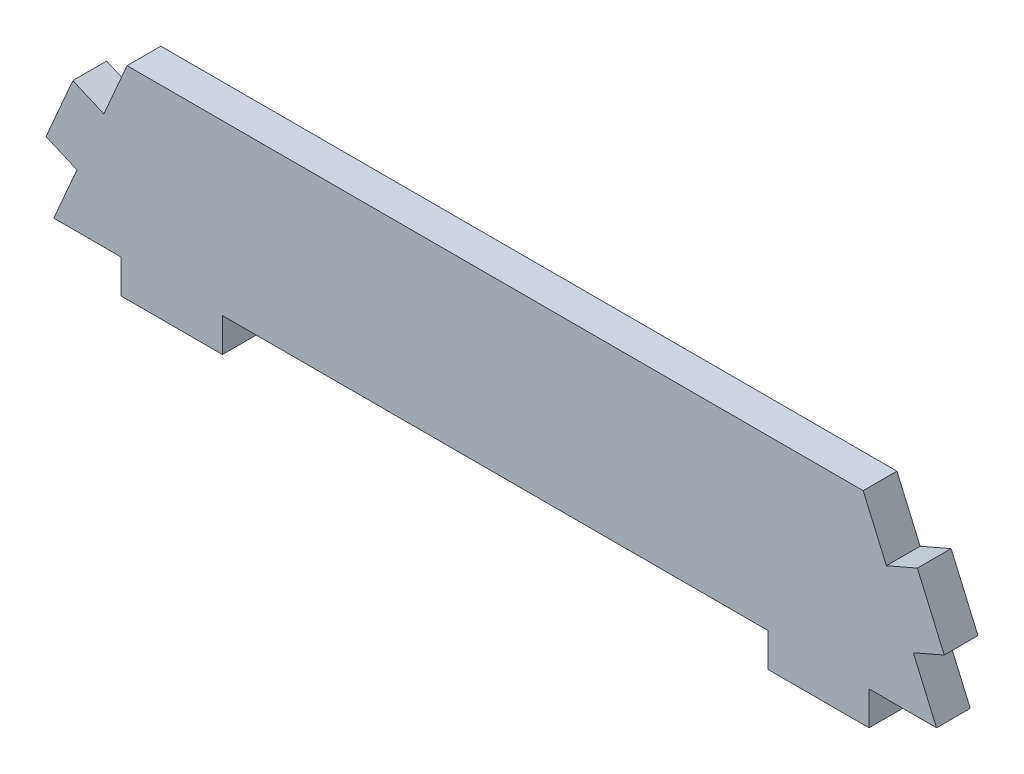
SolidWorks part; units mm, degrees
ref_plane "Front Plane" through (0, 0, 0) normal (0, 0, 1) x (1, 0, 0)
ref_plane "Top Plane" through (0, 0, 0) normal (0, 1, 0) x (1, 0, 0)
ref_plane "Right Plane" through (0, 0, 0) normal (1, 0, 0) x (0, 0, -1)
sketch "Sketch1" plane through (0, 0, 0) normal (0, 0, 1) x (1, 0, 0)
  line L1 (0, 0) -> (40.395, 0)
  line L2 (0, 0) -> (0, 25)
  line L3 (0, 25) -> (54.5281, 25)
  line L4 (65.395, 0) -> (61.9548, 7.9145)
  line L5 (57.9683, 17.0855) -> (62.5539, 19.0787)
  line L6 (62.5539, 19.0787) -> (66.5403, 9.9077)
  line L7 (66.5403, 9.9077) -> (61.9548, 7.9145)
  line L8 (57.9683, 17.0855) -> (54.5281, 25)
  line L9 (55.395, 0) -> (55.395, -5)
  line L10 (55.395, -5) -> (40.395, -5)
  line L11 (40.395, -5) -> (40.395, 0)
  line L12 (55.395, 0) -> (65.395, 0)
  line L13 (57.4221, 18.3421) -> (67.3882, -4.5855) construction
  point P5 (55.8893, 17.7114)
  point P6 (43.602, 17.3692)
  dimension "D1" = 10
  dimension "D2" = 5
  dimension "D4" = 5
  dimension "D5" = 15
  dimension "D6" = 10
  dimension "D7" = 25
extrude "Boss-Extrude1" add sketch "Sketch1" along normal blind 5
mirror "Mirror1" about plane through (0, 0, 5) normal (1, 0, 0) of "Boss-Extrude1"
